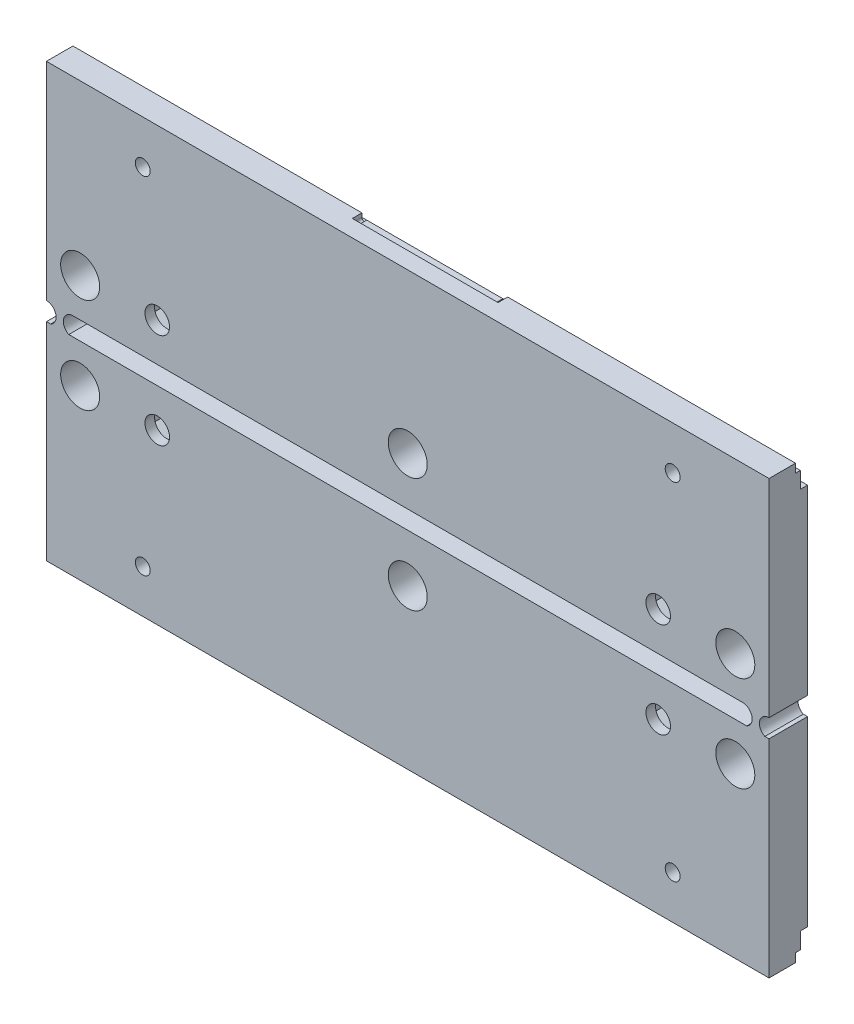
SolidWorks part; units mm, degrees
ref_plane "前视基准面" through (0, 0, 0) normal (0, 0, 1) x (1, 0, 0)
ref_plane "上视基准面" through (0, 0, 0) normal (0, 1, 0) x (1, 0, 0)
ref_plane "右视基准面" through (0, 0, 0) normal (1, 0, 0) x (0, 0, -1)
sketch "前视图草图" plane through (0, 0, 0) normal (0, 0, 1) x (1, 0, 0)
  line L0 (0, 0) -> (8.5179, 0) construction
  line L1 (0, 0) -> (0, 5.4227) construction
sketch "草图2" plane through (0, 0, 0) normal (0, 0, 1) x (1, 0, 0)
  line L0 (0, 0) -> (150, 0)
  line L1 (-200000, 0) -> (200008.5179, 0) construction
  line L2 (150, 0) -> (150, 43)
  line L3 (150, 43) -> (0, 43)
  line L4 (0, -200000) -> (0, 200005.4227) construction
  line L5 (0, 43) -> (0, 0)
  line L6 (75, 43) -> (75, 0) construction
  circle A0 centre (7, 8) radius 4.05
  circle A1 centre (75, 10) radius 4.05
  circle A2 centre (143, 8) radius 4.05
  dimension "D3" = 8
  dimension "D5" = 10
  dimension "D9" = 8.1
  dimension "D10" = 8.1
  dimension "D11" = 8.1
  dimension "D1" = 43
  dimension "D2" = 150
  dimension "D4" = 7
  dimension "D6" = 7
  dimension "D7" = 8
extrude "凸台-拉伸1" add sketch "草图2" along normal blind 8
sketch "草图3" plane through (0, 0, 8) normal (0, 0, 1) x (1, 0, 0)
  line L0 (16.088, 8) -> (31.4805, 8) construction
  line L1 (7, 8) -> (7, 16.8386) construction
  line L2 (143, 8) -> (143, 16.5917) construction
  line L4 (-200000, 0) -> (200008.5179, 0) construction
  circle A2 centre (23, 8) radius 2.55
  circle A3 centre (127, 8) radius 2.55
  dimension "D4" = 5.1
  dimension "D5" = 5.1
  dimension "D1" = 8
  dimension "D2" = 16
  dimension "D3" = 16
extrude "切除-拉伸1" cut sketch "草图3" against normal through all
sketch "草图28" plane through (0, 0, 0) normal (0, 0, -1) x (-1, 0, 0)
  line L0 (-150, 0) -> (-150, 43) construction
  line L1 (-122.9, 5.6329) -> (-122.9, 10.3671)
  line L2 (-122.9, 10.3671) -> (-127, 12.7343)
  line L3 (-127, 12.7343) -> (-131.1, 10.3671)
  line L4 (-131.1, 10.3671) -> (-131.1, 5.6329)
  line L5 (-131.1, 5.6329) -> (-127, 3.2657)
  line L6 (-127, 3.2657) -> (-122.9, 5.6329)
  line L7 (-18.9, 5.6329) -> (-18.9, 10.3671)
  line L8 (-18.9, 10.3671) -> (-23, 12.7343)
  line L9 (-23, 12.7343) -> (-27.1, 10.3671)
  line L10 (-27.1, 10.3671) -> (-27.1, 5.6329)
  line L11 (-27.1, 5.6329) -> (-23, 3.2657)
  line L12 (-23, 3.2657) -> (-18.9, 5.6329)
  circle A0 centre (-127, 8) radius 4.1 construction
  circle A1 centre (-23, 8) radius 4.1 construction
  dimension "D1" = 8.2
extrude "切除-拉伸16" cut sketch "草图28" against normal blind 6
sketch "草图4" plane through (150, 0, 0) normal (1, 0, 0) x (0, 0, -1)
  line L1 (0, -200000) -> (0, 200005.4227) construction
  line L2 (-1.5, 41.2) -> (-2.5, 41.2)
  line L3 (-2.5, 41.2) -> (-2.5, 43)
  line L4 (-8, 43) -> (0, 43) construction
  line L5 (-2.5, 43) -> (0, 43)
  line L6 (-1.5, 41.2) -> (-1.5, 37.8)
  line L7 (-1.5, 37.8) -> (0, 37.8)
  line L8 (0, 37.8) -> (0, 43)
  dimension "D1" = 3.4
  dimension "D2" = 2.5
  dimension "D3" = 1.5
  dimension "D4" = 1.8
extrude "切除-拉伸2" cut sketch "草图4" against normal through all
sketch "草图5" plane through (0, 0, 8) normal (0, 0, 1) x (1, 0, 0)
  line L0 (75, 10) -> (91.5376, 10) construction
  circle A0 centre (75, 10) radius 8 construction
  circle A1 centre (83, 10) radius 1.55
  circle A2 centre (67, 10) radius 1.55
  dimension "D1" = 3.1
  dimension "D2" = 3.1
  dimension "D3" = 16
extrude "切除-拉伸3" [suppressed] cut sketch "草图5" against normal through all
sketch "草图7" plane through (0, 0, 0) normal (0, 0, -1) x (-1, 0, 0)
  line L0 (-40, 12) -> (-40, -8.3696) construction
  line L1 (-23, 10) -> (-23, -2.3368) construction
  line L2 (200000, 0) -> (-200008.5179, 0) construction
  line L6 (-27.05, 10) -> (-27.05, 2.5)
  line L7 (-29.55, 0) -> (-16.45, 0)
  line L8 (-18.95, 2.5) -> (-18.95, 10)
  line L9 (-23, 8) -> (-23, 15.9045) construction
  line L13 (0, -200000) -> (0, 200005.4227) construction
  line L14 (-57, 8) -> (-57, 15.9045) construction
  line L15 (-57, 10) -> (-57, -2.3368) construction
  line L16 (-61.05, 2.5) -> (-61.05, 10)
  line L17 (-50.45, 0) -> (-63.55, 0)
  line L18 (-52.95, 10) -> (-52.95, 2.5)
  arc A1 (-18.95, 10) -> (-27.05, 10) centre (-23, 10) ccw
  arc A4 (-29.55, 0) -> (-27.05, 2.5) centre (-29.55, 2.5) ccw
  arc A5 (-18.95, 2.5) -> (-16.45, 0) centre (-16.45, 2.5) ccw
  arc A7 (-61.05, 2.5) -> (-63.55, 0) centre (-63.55, 2.5) cw
  arc A8 (-50.45, 0) -> (-52.95, 2.5) centre (-50.45, 2.5) cw
  arc A9 (-61.05, 10) -> (-52.95, 10) centre (-57, 10) cw
  dimension "D1" = 40
  dimension "D4" = 8.1
  dimension "D7" = 2.5
  dimension "D8" = 2.5
  dimension "D3" = 10
extrude "切除-拉伸4" [suppressed] cut sketch "草图7" against normal blind 6
sketch "草图8" [suppressed] plane through (0, 0, 0) normal (0, 0, -1) x (-1, 0, 0)
  line L0 (-75, 10) -> (-92.3165, 10) construction
  line L1 (-75, 20) -> (-75, 35.6562) construction
  line L2 (-65.5, 12.85) -> (-84.5, 12.85)
  line L3 (-84.5, 7.15) -> (-65.5, 7.15)
  line L4 (200000, 0) -> (-200008.5179, 0) construction
  line L5 (-150, 0) -> (-150, 28.8) construction
  line L6 (-80.15, 8.3546) -> (-80.15, 11.6454)
  line L7 (-80.15, 11.6454) -> (-83, 13.2909)
  line L8 (-83, 13.2909) -> (-85.85, 11.6454)
  line L9 (-85.85, 11.6454) -> (-85.85, 8.3546)
  line L10 (-85.85, 8.3546) -> (-83, 6.7091)
  line L11 (-83, 6.7091) -> (-80.15, 8.3546)
  line L12 (-64.15, 8.3546) -> (-64.15, 11.6454)
  line L13 (-64.15, 11.6454) -> (-67, 13.2909)
  line L14 (-67, 13.2909) -> (-69.85, 11.6454)
  line L15 (-69.85, 11.6454) -> (-69.85, 8.3546)
  line L16 (-69.85, 8.3546) -> (-67, 6.7091)
  line L17 (-67, 6.7091) -> (-64.15, 8.3546)
  line L19 (0, -200000) -> (0, 200005.4227) construction
  arc A0 (-65.5, 7.15) -> (-65.5, 12.85) centre (-65.5, 10) ccw
  arc A1 (-84.5, 12.85) -> (-84.5, 7.15) centre (-84.5, 10) ccw
  circle A2 centre (-83, 10) radius 2.85 construction
  circle A3 centre (-67, 10) radius 2.85 construction
  dimension "D1" = 5.7
  dimension "D2" = 9.5
  dimension "D3" = 9.5
  dimension "D4" = 10
  dimension "D5" = 5.7
  dimension "D6" = 75
extrude "切除-拉伸5" [suppressed] cut sketch "草图8" against normal blind 4.5 contours L9 L10 L11 L6 L7 L8 | L17 L12 L13 L14 L15 L16
sketch "草图20" plane through (0, 0, 0) normal (0, 0, -1) x (-1, 0, 0)
  circle A0 centre (-75, 10) radius 5.5
  dimension "D1" = 11
sketch "草图25" plane through (0, 0, 0) normal (0, 0, -1) x (-1, 0, 0)
  line L0 (-51.4471, 34) -> (-40.1512, 34) construction
  line L1 (-130, 37.1428) -> (-130, 21.9179) construction
  line L2 (-20, 37.1428) -> (-20, 21.9179) construction
  line L3 (0, 43) -> (-150, 43) construction
  line L4 (-150, 0) -> (-150, 37.8) construction
  line L5 (0, -200000) -> (0, 200005.4227) construction
  circle A0 centre (-130, 34) radius 1.55
  circle A1 centre (-20, 34) radius 1.55
  dimension "D4" = 3.1
  dimension "D5" = 3.1
  dimension "D1" = 9
  dimension "D2" = 20
  dimension "D3" = 20
extrude "切除-拉伸13" cut sketch "草图25" against normal through all
sketch "草图19" plane through (0, 0, 2.5) normal (0, 0, -1) x (-1, 0, 0)
  line L0 (0, 43) -> (-150, 43) construction
  line L1 (-60, 43) -> (-90.2479, 43)
  line L2 (-60, 43) -> (-60, 42.2)
  line L3 (-61, 42.2) -> (-89.2479, 42.2)
  line L4 (-90.2479, 43) -> (-90.2479, 42.2)
  line L6 (-90.2479, 81.6491) -> (-90.2479, -28.0472) construction
  line L7 (0, 41.2) -> (-150, 41.2) construction
  line L8 (-56.3335, 41.7) -> (-52.9089, 41.7) construction
  line L9 (-90.2479, 1028.5823) -> (-90.2479, 42.2) construction
  line L10 (-60, 1028.5823) -> (-60, 41.7) construction
  line L11 (-90.2479, 41.7) -> (-90.2479, -973.3) construction
  line L12 (-60, 41.7) -> (-60, -973.3) construction
  arc A3 (-90.2479, 42.2) -> (-89.2479, 42.2) centre (-89.7479, 42.2) ccw
  arc A6 (-61, 42.2) -> (-60, 42.2) centre (-60.5, 42.2) ccw
  dimension "D3" = 1
  dimension "D4" = 1
  dimension "D5" = 30.2479
  dimension "D6" = 15
  dimension "D2" = 0.8
  dimension "D1" = 0.5
extrude "切除-拉伸11" cut sketch "草图19" against normal blind 2
sketch "草图22" plane through (0, 0, 8) normal (0, 0, 1) x (1, 0, 0)
  line L1 (0, -200000) -> (0, 200005.4227) construction
  line L2 (0, -4) -> (5.5, -4)
  line L4 (150, 0) -> (144.5, 0)
  line L5 (3.5, 1.9875) -> (3.5, -4.1402) construction
  line L6 (146.5, -11.5647) -> (146.5, -5.1636) construction
  line L7 (150, 0) -> (150, 43) construction
  line L8 (144.5, -4) -> (150, -4)
  line L9 (5.5, 0) -> (0, 0)
  line L10 (148, -2.9635) -> (148, -4.3032) construction
  line L11 (2, -8.393) -> (2, -15.1693) construction
  arc A0 (5.5, 0) -> (5.5, -4) centre (5.5, -2) ccw
  arc A1 (144.5, -4) -> (144.5, 0) centre (144.5, -2) ccw
  arc A2 (0, -4) -> (0, 0) centre (0, -2) ccw
  arc A3 (150, 0) -> (150, -4) centre (150, -2) ccw
  dimension "D1" = 3.5
  dimension "D2" = 3.5
  dimension "D3" = 4
  dimension "D4" = 2
  dimension "D5" = 2
extrude "凸台-拉伸2" add sketch "草图22" against normal blind 8
ref_plane "基准面1" through (0, -1.9, 0) normal (0, -1, 0) x (-1, 0, 0)
mirror "镜向2" about plane through (0, -1.9, 0) normal (0, -1, 0) of "切除-拉伸16", "凸台-拉伸1", "切除-拉伸2", "切除-拉伸11", "切除-拉伸13", "切除-拉伸1"
sketch "草图23" plane through (0, 0, 0) normal (0, 0, -1) x (-1, 0, 0)
  line L0 (-80, 0) -> (0, 0)
  line L1 (0, 0) -> (0, -4)
  line L2 (0, -4) -> (-80, -4)
  line L3 (-80, -4) -> (-80, 0)
sketch "草图26" [suppressed] plane through (0, 0, 0) normal (0, 0, -1) x (-1, 0, 0)
  circle A0 centre (-143, -12) radius 6.025
  circle A1 centre (-7, -12) radius 6.025
  dimension "D1" = 12.05
  dimension "D2" = 12.05
extrude "切除-拉伸14" [suppressed] cut sketch "草图26" against normal through all
sketch "草图27" [suppressed] plane through (0, 0, 0) normal (0, 0, -1) x (-1, 0, 0)
  line L0 (-136, 28.8) -> (-136, -32.8) construction
  line L3 (-150, 12) -> (0, 12) construction
  line L4 (-150, 0) -> (-150, 28.8) construction
  line L5 (0, -200000) -> (0, 200005.4227) construction
  line L6 (-75, 28.8) -> (-75, -32.8) construction
  line L7 (0, 28.8) -> (-150, 28.8) construction
  line L8 (0, -32.8) -> (-150, -32.8) construction
  line L9 (0, 28.8) -> (-150, 28.8) construction
  line L10 (0, -32.8) -> (-150, -32.8) construction
  line L11 (-150, -16) -> (0, -16) construction
  line L12 (-150, -4) -> (-150, -32.8) construction
  line L13 (200000, 0) -> (-200008.5179, 0) construction
  line L14 (0, -4) -> (-80, -4) construction
  circle A0 centre (-136, 12) radius 3
  circle A1 centre (-136, -16) radius 1.55
  circle A2 centre (-14, -16) radius 1.55
  circle A3 centre (-14, 12) radius 3
  dimension "D4" = 3.1
  dimension "D5" = 6
  dimension "D1" = 12
  dimension "D2" = 12
  dimension "D3" = 14
extrude "切除-拉伸15" [suppressed] cut sketch "草图27" against normal through all
sketch "草图24" [suppressed] plane through (0, 0, 8) normal (0, 0, 1) x (1, 0, 0)
  line L0 (80, -4) -> (80, 0)
  line L1 (80, 0) -> (0, 0)
  line L2 (0, 0) -> (0, -4)
  line L3 (0, -4) -> (80, -4)
extrude "切除-拉伸17" [suppressed] cut sketch "草图20" against normal through all
